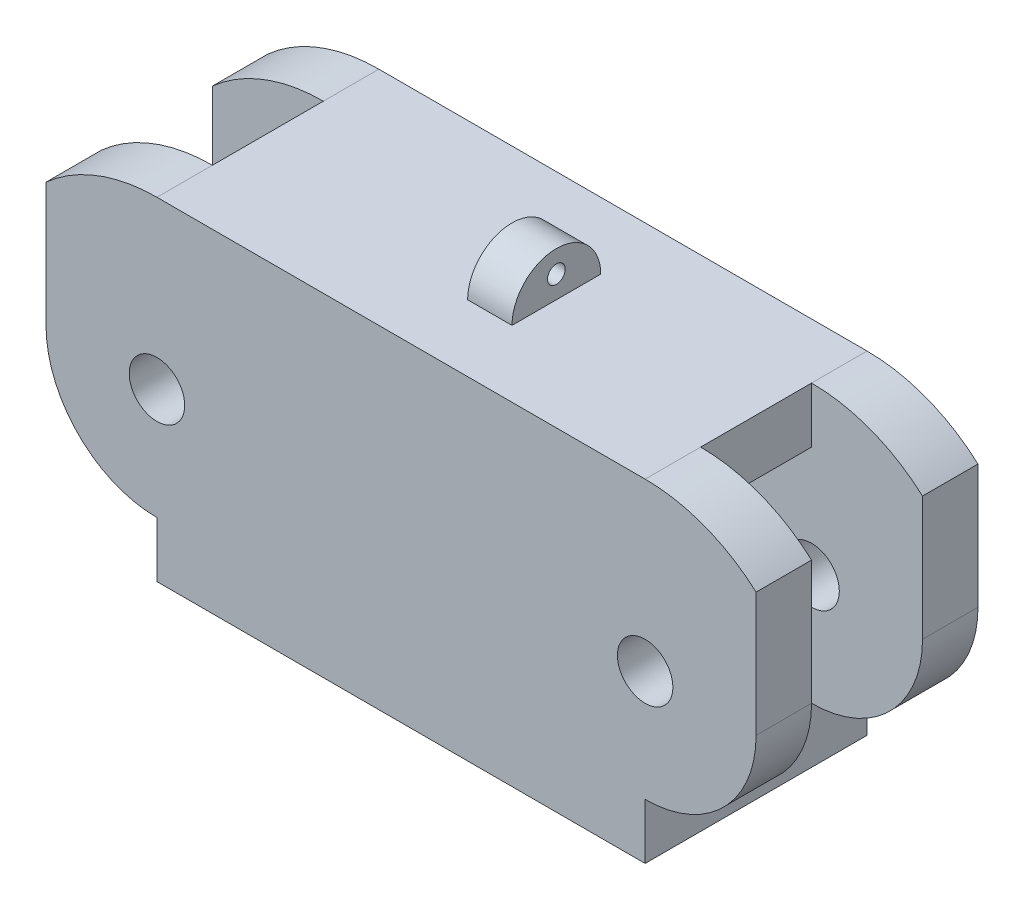
SolidWorks part; units mm, degrees
ref_plane "Front Plane" through (0, 0, 0) normal (0, 0, 1) x (1, 0, 0)
ref_plane "Top Plane" through (0, 0, 0) normal (0, 1, 0) x (1, 0, 0)
ref_plane "Right Plane" through (0, 0, 0) normal (1, 0, 0) x (0, 0, -1)
ref_plane "Right Side Plane" through (0, 0, 9.525) normal (0, 0, 1) x (1, 0, 0)
ref_plane "Inside Plane" through (0, 19.05, 0) normal (0, 1, 0) x (1, 0, 0)
sketch "Sketch1" plane through (0, 0, 0) normal (0, 1, 0) x (1, 0, 0)
  line L1 (-23.495, 9.525) -> (24.13, 9.525)
  line L2 (-23.495, 9.525) -> (-23.495, -9.525)
  line L3 (-23.495, -9.525) -> (24.13, -9.525)
  line L4 (24.13, 9.525) -> (24.13, -9.525)
  dimension "D1" = 19.05
  dimension "D2" = 47.625
  dimension "D3" = 23.495
  dimension "D4" = 9.525
extrude "Boss-Extrude1" add sketch "Sketch1" along normal blind 19.05
sketch "Sketch2" plane through (0, 0, 9.525) normal (0, 0, 1) x (1, 0, 0)
  line L2 (-23.495, 19.05) -> (24.13, 19.05) construction
  line L3 (-23.495, 19.05) -> (-23.495, 0) construction
  line L4 (-23.495, 0) -> (24.13, 0) construction
  line L5 (0, 0) -> (0, 19.05) construction
  circle A0 centre (-13.97, 9.525) radius 1.5875
  arc A1 (-13.97, 19.05) -> (-13.97, 0) centre (-13.97, 9.525) ccw
  arc A2 (-13.97, 19.05) -> (-13.97, 0) centre (-21.8333, 9.525) ccw
  arc A3 (13.97, 19.05) -> (13.97, 0) centre (21.8333, 9.525) cw
  arc A4 (13.97, 19.05) -> (13.97, 0) centre (13.97, 9.525) cw
  circle A5 centre (13.97, 9.525) radius 1.5875
  point P19 (0, 0)
extrude "Cut-Extrude1" cut sketch "Sketch2" against normal blind 19.05
sketch "Sketch9" plane through (0, 19.05, 0) normal (0, 1, 0) x (1, 0, 0)
  line L1 (0, -2.54) -> (2.54, -2.54)
  line L2 (0, -2.54) -> (0, 2.54)
  line L3 (0, 2.54) -> (2.54, 2.54)
  line L4 (2.54, -2.54) -> (2.54, 2.54)
  dimension "D1" = 5.08
  dimension "D2" = 2.54
  dimension "D3" = 0
  dimension "D4" = 2.54
extrude "Boss-Extrude2" add sketch "Sketch9" along normal blind 2.54
sketch "Sketch3" plane through (0, 0, 0) normal (1, 0, 0) x (0, 0, -1)
  line L0 (-9.525, 19.05) -> (-9.525, 0) construction
  line L1 (3.175, 15.875) -> (-3.175, 15.875)
  line L2 (3.175, 15.875) -> (3.175, 3.175)
  line L3 (3.175, 3.175) -> (-3.175, 3.175)
  line L4 (-3.175, 15.875) -> (-3.175, 3.175)
  line L5 (9.525, 19.05) -> (-9.525, 19.05) construction
  line L6 (9.525, 0) -> (9.525, 19.05) construction
  line L7 (9.525, 0) -> (-9.525, 0) construction
  line L8 (-2.54, 21.59) -> (2.54, 21.59) construction
  line L9 (-2.54, 21.59) -> (-2.54, 19.05) construction
  arc A0 (-2.54, 19.05) -> (2.54, 19.05) centre (0, 19.05) cw
  circle A1 centre (0, 20.32) radius 0.508
  arc A3 (-2.54, 19.05) -> (2.54, 19.05) centre (0, 20.9413) cw
  dimension "D5" = 1.27
  dimension "D1" = 6.35
  dimension "D2" = 3.175
  dimension "D3" = 6.35
  dimension "D4" = 3.175
  dimension "D6" = 2.54
extrude "Cut-Extrude2" cut sketch "Sketch3" against normal mid plane 76.2
sketch "Sketch4" plane through (0, 19.05, 0) normal (0, 1, 0) x (1, 0, 0)
  line L0 (-13.97, 9.525) -> (-13.97, -9.525) construction
  line L1 (-29.3612, -9.525) -> (-13.97, -9.525)
  line L2 (-29.3612, -9.525) -> (-29.3612, -6.35)
  line L3 (-29.3612, -6.35) -> (-13.97, -6.35)
  line L5 (13.97, 9.525) -> (13.97, -9.525) construction
  line L6 (-13.97, 6.35) -> (-31.5103, 6.35)
  line L8 (-11.1125, 9.525) -> (-31.5103, 9.525)
  line L9 (-31.5103, 6.35) -> (-31.5103, 9.525)
  line L10 (28.4066, -9.525) -> (1.5875, -9.525)
  line L11 (28.4066, -9.525) -> (28.4066, -6.35)
  line L12 (28.4066, -6.35) -> (1.5875, -6.35)
  line L14 (23.495, 9.525) -> (13.97, 9.525) construction
  line L15 (1.5875, 6.35) -> (30.675, 6.35)
  line L17 (1.5875, 9.525) -> (30.675, 9.525)
  line L18 (30.675, 6.35) -> (30.675, 9.525)
  line L20 (-13.97, 9.525) -> (-23.495, 9.525) construction
  line L22 (13.97, -3.175) -> (29.168, -3.175)
  line L23 (13.97, -3.175) -> (13.97, 3.175)
  line L24 (13.97, 3.175) -> (29.168, 3.175)
  line L25 (29.168, -3.175) -> (29.168, 3.175)
  line L30 (1.5875, -9.525) -> (-13.97, -9.525)
  line L31 (-13.97, -6.35) -> (1.5875, -6.35)
  line L32 (1.5875, 6.35) -> (-13.97, 6.35)
  line L33 (-11.1125, 9.525) -> (1.5875, 9.525)
  dimension "D1" = 3.175
  dimension "D2" = 3.175
  dimension "D5" = 3.175
  dimension "D6" = 3.175
extrude "Cut-Extrude3" cut sketch "Sketch4" against normal blind 43.18
sketch "Sketch6" plane through (0, 0, 9.525) normal (0, 0, 1) x (1, 0, 0)
  line L1 (13.97, 0) -> (31.9801, 0)
  line L2 (13.97, 0) -> (13.97, 3.175)
  line L4 (31.9801, 0) -> (31.9801, 3.175)
  line L6 (20.32, 9.525) -> (20.32, 24.3707)
  line L7 (20.32, 24.3707) -> (27.1836, 13.8085)
  line L8 (27.1836, 13.8085) -> (31.9801, 3.175)
  line L9 (23.495, 9.525) -> (20.32, 9.525) construction
  line L10 (-13.97, 0) -> (-13.97, 3.175)
  line L13 (-20.32, 9.525) -> (-20.32, 20.9428)
  line L14 (-20.32, 20.9428) -> (-28.9216, 11.7677)
  line L15 (-28.9216, 11.7677) -> (-28.9216, 0)
  line L16 (-28.9216, 0) -> (-13.97, 0)
  arc A0 (13.97, 0) -> (13.97, 19.05) centre (13.97, 9.525) ccw construction
  arc A1 (20.32, 9.525) -> (13.97, 3.175) centre (13.97, 9.525) cw
  arc A3 (-13.97, 3.175) -> (-20.32, 9.525) centre (-13.97, 9.525) cw
  arc A4 (-13.97, 19.05) -> (-13.97, 0) centre (-13.97, 9.525) ccw construction
  point P9 (23.495, 9.525)
  point P21 (-23.495, 9.525)
  dimension "D5" = 3.175
  dimension "D1" = 3.175
  dimension "D2" = 3.175
  dimension "D3" = 3.175
  dimension "D4" = 3.175
extrude "Cut-Extrude4" cut sketch "Sketch6" against normal blind 19.05
sketch "Sketch7" plane through (0, 19.05, 0) normal (0, 1, 0) x (1, 0, 0)
  line L0 (-13.97, 6.35) -> (-13.97, -6.35) construction
  line L1 (-27.7489, -3.175) -> (-13.97, -3.175)
  line L2 (-27.7489, -3.175) -> (-27.7489, 3.175)
  line L3 (-27.7489, 3.175) -> (-13.97, 3.175)
  line L4 (-13.97, -3.175) -> (-13.97, 3.175)
  line L5 (-20.32, -6.35) -> (-13.97, -6.35) construction
  line L6 (-13.97, 6.35) -> (-20.32, 6.35) construction
  point P5 (-1.5875, -6.35)
  point P13 (0, 0)
  point P16 (0, 0)
  dimension "D1" = 0
  dimension "D2" = 3.175
  dimension "D3" = 3.175
extrude "Cut-Extrude5" cut sketch "Sketch7" against normal blind 3.81
